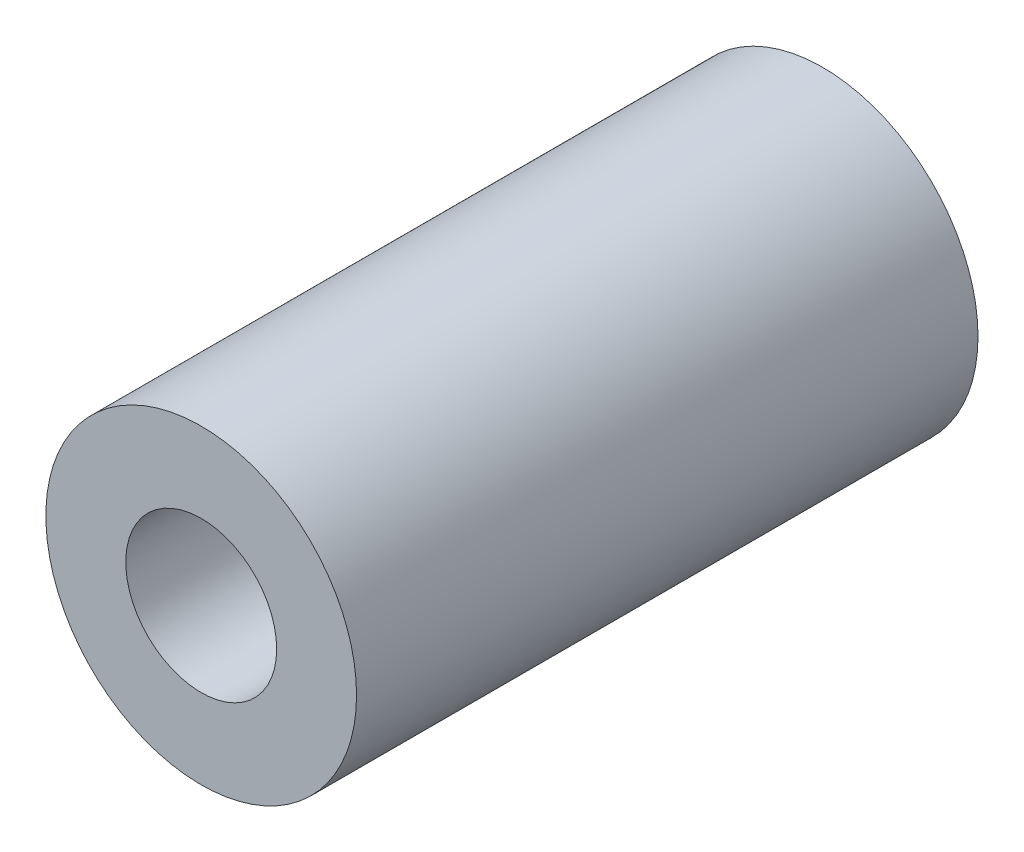
SolidWorks part; units mm, degrees
ref_plane "Plano frontal" through (0, 0, 0) normal (0, 0, 1) x (1, 0, 0)
ref_plane "Plano superior" through (0, 0, 0) normal (0, 1, 0) x (1, 0, 0)
ref_plane "Plano direito" through (0, 0, 0) normal (1, 0, 0) x (0, 0, -1)
sketch "Esboço1" plane through (0, 0, 0) normal (0, 0, 1) x (1, 0, 0)
  circle A0 centre (0, 0) radius 1.7
  circle A1 centre (0, 0) radius 3.5
extrude "Ressalto-extrusão1" add sketch "Esboço1" along normal blind 14
